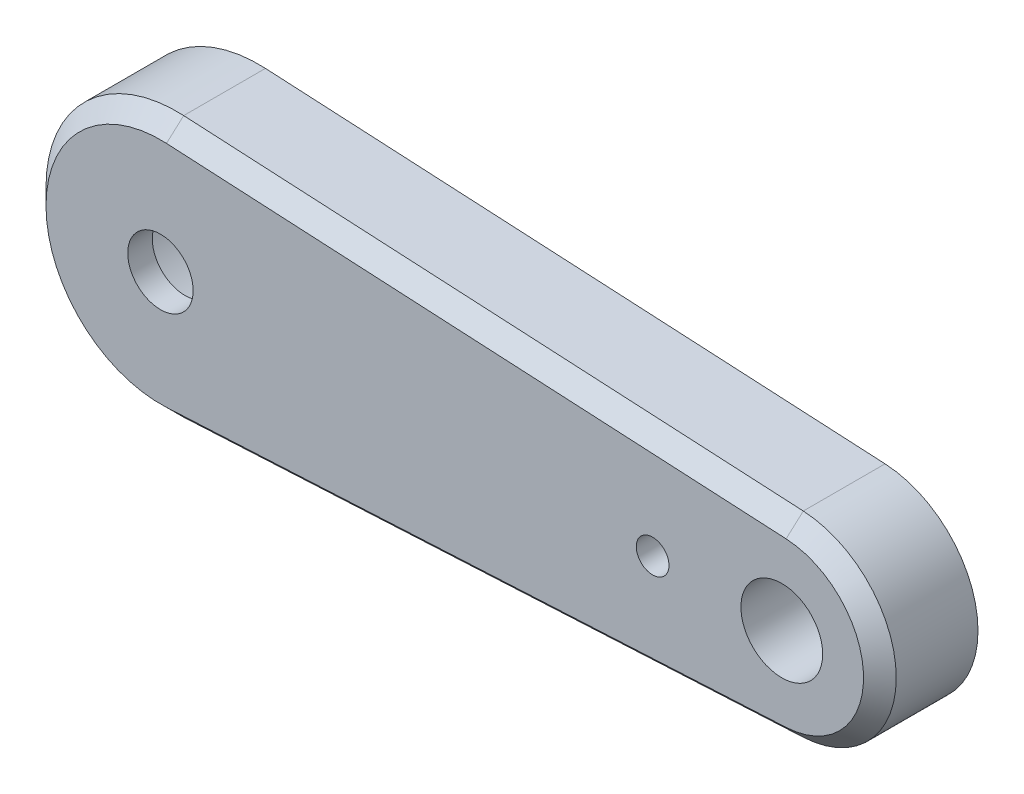
SolidWorks part; units mm, degrees
ref_plane "Alzado" through (0, 0, 0) normal (0, 0, 1) x (1, 0, 0)
ref_plane "Planta" through (0, 0, 0) normal (0, 1, 0) x (1, 0, 0)
ref_plane "Vista lateral" through (0, 0, 0) normal (1, 0, 0) x (0, 0, -1)
sketch "Croquis1" plane through (0, 0, 0) normal (0, 0, 1) x (1, 0, 0)
  line L0 (0, 0) -> (16185.8284, 0) construction
  line L1 (0, 0) -> (19, 0) construction
  line L2 (0.2105, 3.9945) -> (19.1579, 2.9958)
  line L3 (0.2105, -3.9945) -> (19.1579, -2.9958)
  circle A0 centre (0, 0) radius 1
  circle A1 centre (19, 0) radius 1.25
  arc A3 (19.1579, -2.9958) -> (19.1579, 2.9958) centre (19, 0) ccw
  arc A4 (0.2105, 3.9945) -> (0.2105, -3.9945) centre (0, 0) ccw
  point P5 (9.5, 0)
  dimension "D2" = 3
  dimension "D3" = 2.5
  dimension "D4" = 2
  dimension "D5" = 8
  dimension "D1" = 19
extrude "Saliente-Extruir1" add sketch "Croquis1" along normal blind 3
sketch "Croquis2" plane through (0, 0, 0) normal (0, 0, -1) x (-1, 0, 0)
  line L0 (-15.1547, 2.2476) -> (-0.1372, 2.9468)
  line L3 (-15.1547, -2.2476) -> (-0.1372, -2.9468)
  line L4 (-0.196, 0) -> (-50000.196, 0) construction
  arc A2 (-0.1372, 2.9468) -> (-0.1372, -2.9468) centre (0, 0) cw
  arc A3 (-15.1547, 2.2476) -> (-15.1547, -2.2476) centre (-15.05, 0) ccw
  dimension "D1" = 2.95
  dimension "D2" = 2.25
  dimension "D3" = 15.05
extrude "Cortar-Extruir1" cut sketch "Croquis2" against normal blind 1.5
sketch "Croquis3" plane through (0, 0, 1.5) normal (0, 0, -1) x (-1, 0, 0)
  circle A0 centre (0, 0) radius 2.1
  dimension "D1" = 4.2
extrude "Cortar-Extruir2" cut sketch "Croquis3" against normal blind 0.75
sketch "Croquis4" plane through (0, 0, 1.5) normal (0, 0, -1) x (-1, 0, 0)
  circle A0 centre (-15.05, 0) radius 0.5
  dimension "D1" = 1
extrude "Cortar-Extruir3" cut sketch "Croquis4" against normal through all
chamfer "Chaflán1" distance 0.5 angle 45 4 edges at (9.6842, -3.4951, 3) (22, 0, 3) (9.6842, 3.4951, 3) (-4, 0, 3)
